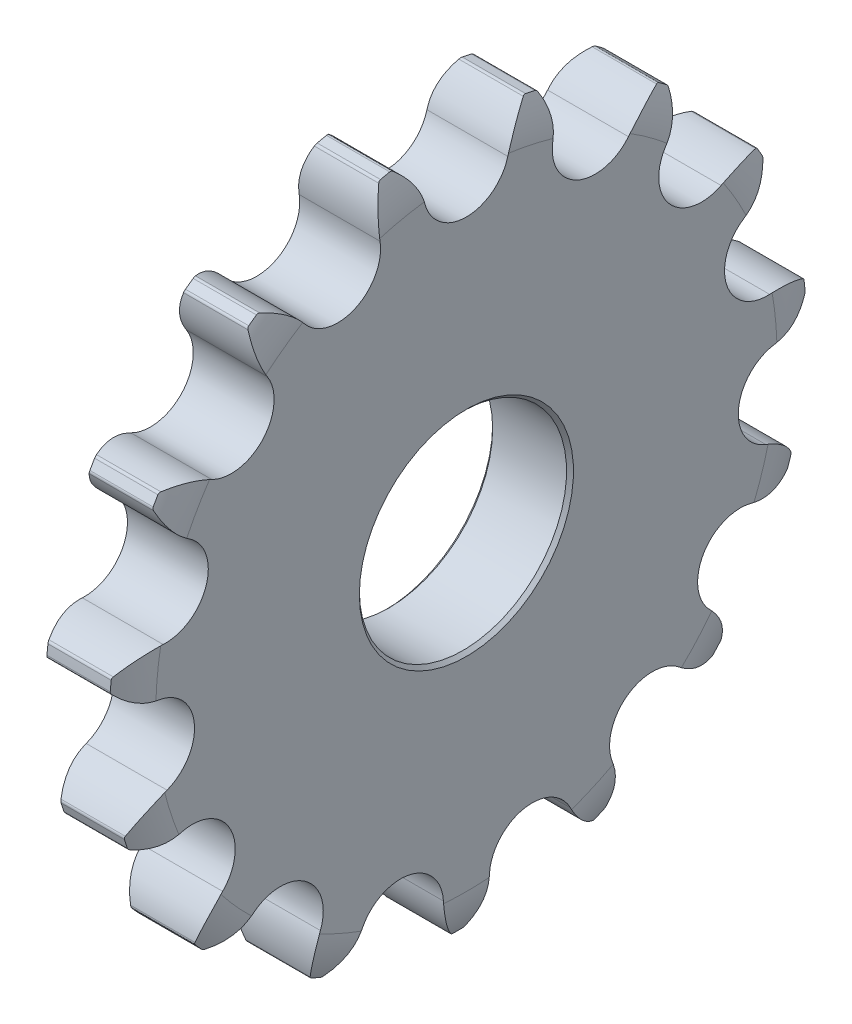
SolidWorks part; units mm, degrees
material "AISI 304"
ref_plane "前基準面" through (0, 0, 0) normal (0, 0, 1) x (1, 0, 0)
ref_plane "上基準面" through (0, 0, 0) normal (0, 1, 0) x (1, 0, 0)
ref_plane "右基準面" through (0, 0, 0) normal (1, 0, 0) x (0, 0, -1)
sketch "草圖1" plane through (0, 0, 0) normal (0, 0, 1) x (1, 0, 0)
  line L0 (0, 0) -> (39318.8892, 0) construction
  line L1 (0, 0) -> (0, 50.5) construction
  line L2 (-5.85, 15) -> (5.85, 15)
  line L3 (5.85, 15) -> (5.85, 44.9642)
  line L4 (4.58, 50.5) -> (-4.58, 50.5)
  line L5 (-5.85, 15) -> (-5.85, 44.9642)
  arc A0 (5.85, 44.9642) -> (4.58, 50.5) centre (-6.85, 44.9642) ccw
  arc A1 (-5.85, 44.9642) -> (-4.58, 50.5) centre (6.85, 44.9642) cw
  point P15 (0, 15)
  dimension "D4" = 12.7
  dimension "D1" = 30
  dimension "D2" = 101
  dimension "D3" = 11.7
  dimension "D5" = 1.27
revolve "旋轉1" add sketch "草圖1" angle 360 about L0
sketch "草圖2" plane through (0, 0, 0) normal (1, 0, 0) x (0, 0, -1)
  line L0 (0, 0) -> (0, 64.3116) construction
  line L3 (5.9936, 44.204) -> (0, 21.8357) construction
  circle A0 centre (0, 0) radius 45.81 construction
  circle A1 centre (0, 0) radius 39.605 construction
  arc A2 (5.9936, 44.204) -> (-5.9936, 44.204) centre (0, 45.81) cw
  circle A4 centre (0, 0) radius 50.5 construction
  arc A6 (9.6033, 49.5785) -> (-9.6033, 49.5785) centre (0, 0) ccw
  arc A7 (5.9936, 44.204) -> (9.6033, 49.5785) centre (15.6528, 41.6158) cw
  arc A8 (-5.9936, 44.204) -> (-9.6033, 49.5785) centre (-15.6528, 41.6158) ccw
  dimension "D1" = 91.62
  dimension "D2" = 79.21
  dimension "D3" = 15
  dimension "D4" = 10
extrude "除料-伸長1" cut sketch "草圖2" against normal mid plane 12
fillet "圓角1" radius 0.5 2 edges at (0, 49.5785, 9.6033) (0, 49.5785, -9.6033)
chamfer "導角1" distance 0.5 angle 45 2 edges at (-5.85, 0, 15) (5.85, 0, 15)
pattern_circular "環狀複製排列1" count 15 over 360 about axis through (0, 0, 0) along (1, 0, 0) of "除料-伸長1", "圓角1"
sketch "草圖3" plane through (0, 0, 0) normal (1, 0, 0) x (0, 0, -1)
  line L0 (0, 0) -> (0, 45.8127) construction
  line L1 (0, 45.8127) -> (18.6337, 41.852) construction
  line L2 (18.6337, 41.852) -> (0, 0) construction
  arc A0 (12.504, 42.8202) -> (23.4548, 37.9446) centre (18.6326, 41.8495) ccw construction
  circle A1 centre (0, 45.8127) radius 5.955 construction
  point P7 (16.1088, 36.181)
  dimension "D2" = 11.91
  dimension "D1" = 19.05
